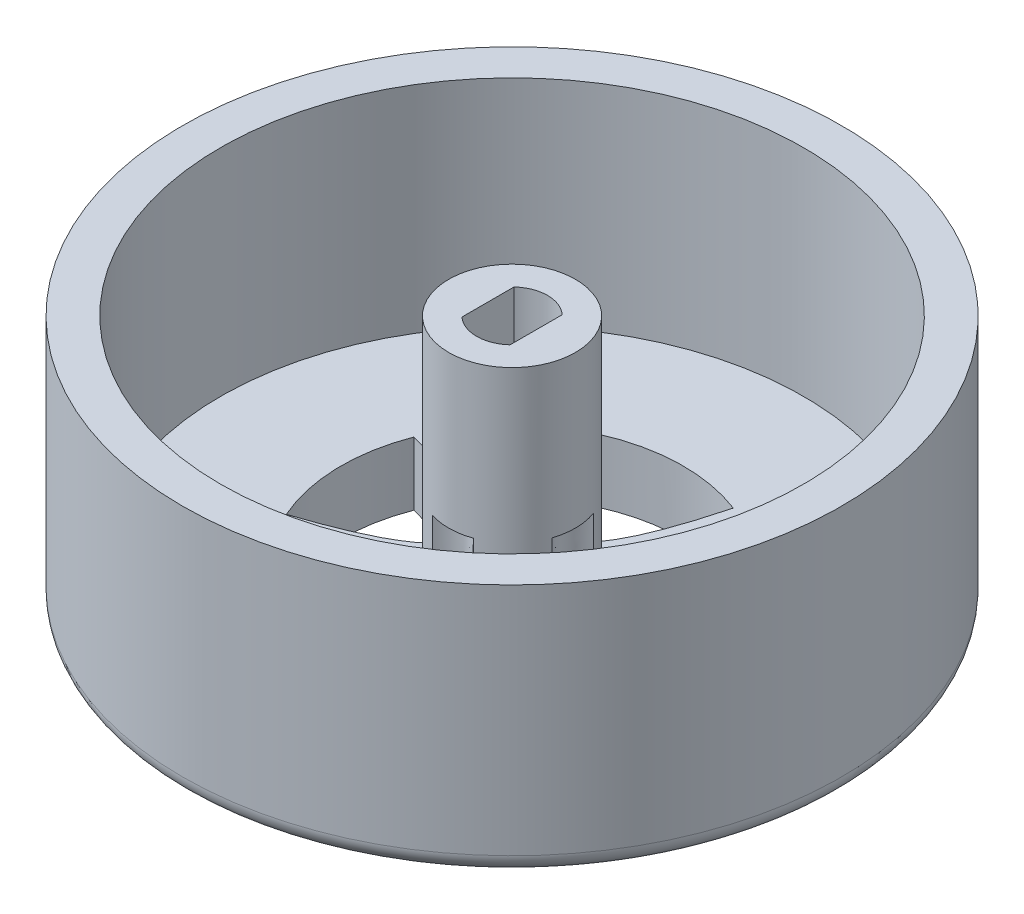
SolidWorks part; units mm, degrees
ref_plane "Alzado" through (0, 0, 0) normal (0, 0, 1) x (1, 0, 0)
ref_plane "Planta" through (0, 0, 0) normal (0, 1, 0) x (1, 0, 0)
ref_plane "Vista lateral" through (0, 0, 0) normal (1, 0, 0) x (0, 0, -1)
sketch "Croquis1" plane through (0, 0, 0) normal (0, 1, 0) x (1, 0, 0)
  circle A0 centre (0, 0) radius 26
  dimension "D1" = 52
extrude "Saliente-Extruir1" add sketch "Croquis1" along normal blind 20
shell "Vaciado1" thickness 3
fillet "Redondeo1" radius 1.5 1 edges at (0, 0, 26)
sketch "Croquis2" plane through (0, 0, 0) normal (0, -1, 0) x (1, 0, 0)
  circle A0 centre (0, 0) radius 15
  dimension "D1" = 30
extrude "Saliente-Extruir2" add sketch "Croquis2" along normal blind 2
fillet "Redondeo2" radius 1.5 1 edges at (0, -2, -15)
sketch "Croquis3" plane through (0, -2, 0) normal (0, -1, 0) x (1, 0, 0)
  circle A0 centre (0, 0) radius 1.55
  dimension "D1" = 3.1
sketch "Croquis5" plane through (0, 3, 0) normal (0, 1, 0) x (1, 0, 0)
  circle A0 centre (0, 0) radius 5
  dimension "D1" = 10
extrude "Saliente-Extruir3" add sketch "Croquis5" along normal up to surface (17 mm away) up to face at (0, 20, 23)
sketch "Croquis6" plane through (0, 20, 0) normal (0, 1, 0) x (1, 0, 0)
  line L2 (-1.9, 2.0567) -> (-1.9, -2.0567)
  line L4 (1.9, 2.0567) -> (1.9, -2.0567)
  circle A0 centre (0, 0) radius 2.8
  dimension "D1" = 5.6
extrude "Cortar-Extruir3" cut sketch "Croquis6" against normal blind 7 contours L4 A0 L2
hole_wizard "Refrentado para tornillo con cabeza troncocónica de M2.51" positions "Croquis3D3" profile "Croquis10" counterbore size "M2.5" standard "Ansi Metric" end condition through all
sketch3d "Croquis3D3"
  point P0 (0, 0, 0)
  point P4 (0, -2, 0)
sketch "Croquis10" plane through (0, -2, 0) normal (1, 0, 0) x (0, 0, -1)
  line L0 (0, 0) -> (0, 22)
  line L1 (0, 22) -> (1.45, 22)
  line L3 (1.45, 22) -> (1.45, 2.1)
  line L4 (1.45, 2.1) -> (3, 2.1)
  line L5 (3, 2.1) -> (3, 0)
  line L7 (3, 0) -> (0, 0)
  line L11 (0, -6.35) -> (0, 107.95) construction
  dimension "Diámetro de taladro hasta el siguiente" = 2.9
  dimension "Profundidad de taladro hasta el siguiente" = 22
  dimension "Diámetro de refrentado" = 6
  dimension "Profundidad de refrentado" = 2.1
sketch "Croquis4" plane through (0, -2, 0) normal (0, -1, 0) x (1, 0, 0)
  circle A0 centre (0, 0) radius 15
  circle A1 centre (0, 0) radius 15 construction
  circle A2 centre (0, 0) radius 15 construction
  spline S0 degree 2 poles (-4.9054, 14.1752) (-0.3276, -6.4295) (5.6447, 13.8974) knots 0 0 0 1 1 1
  spline S1 degree 2 poles (17.0103, 5.8865) (-9.2366, 0.4054) (16.6769, -6.7736) knots 0 0 0 1 1 1
  spline S2 degree 2 poles (5.8865, -17.0103) (0.4054, 9.2366) (-6.7736, -16.6769) knots 0 0 0 1 1 1
  spline S3 degree 2 poles (-17.0103, -5.8865) (9.2366, -0.4054) (-16.6769, 6.7736) knots 0 0 0 1 1 1
  circle M3 centre (0, 0) radius 13.5
extrude "Cortar-Extruir5" cut sketch "Croquis4" against normal blind 10 contours S2 M3 | S3 M3 | S0 M3 | S1 M3
sketch "Croquis11" plane through (0, 0.1, 0) normal (0, -1, 0) x (-1, 0, 0)
  circle A0 centre (0, 0) radius 2.59
  dimension "D1" = 5.18
sketch "Croquis12" plane through (0, 0.1, 0) normal (0, -1, 0) x (1, 0, 0)
  circle A0 centre (0, 0) radius 2.9756
extrude "Cortar-Extruir4" cut sketch "Croquis12" against normal blind 12
